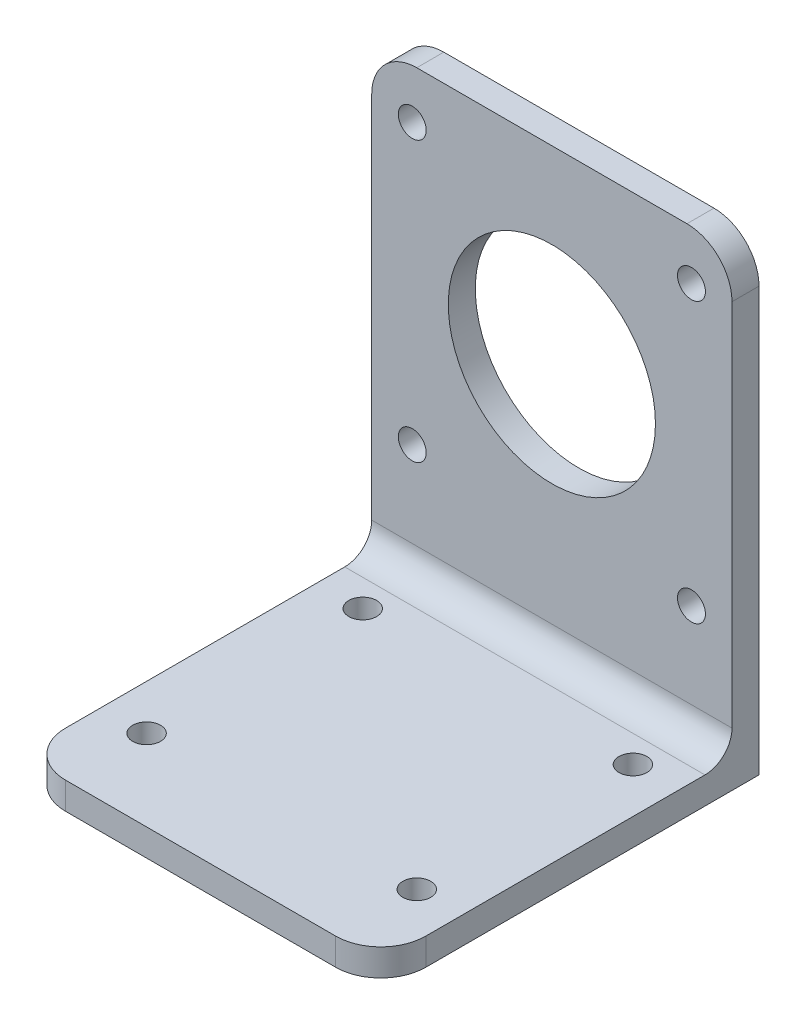
SolidWorks part; units mm, degrees
material "可锻铸铁"
ref_plane "前视基准面" through (0, 0, 0) normal (0, 0, 1) x (1, 0, 0)
ref_plane "上视基准面" through (0, 0, 0) normal (0, 1, 0) x (1, 0, 0)
ref_plane "右视基准面" through (0, 0, 0) normal (1, 0, 0) x (0, 0, -1)
sketch "草图1" plane through (0, 0, 0) normal (0, 1, 0) x (1, 0, 0)
  line L1 (-20, 21) -> (20, 21)
  line L2 (-20, 21) -> (-20, -21)
  line L3 (-20, -21) -> (20, -21)
  line L4 (20, 21) -> (20, -21)
  line L5 (-20, 21) -> (20, -21) construction
  line L6 (-20, -21) -> (20, 21) construction
  line L7 (-15, 12) -> (15, 12) construction
  line L8 (-15, 12) -> (-15, -12) construction
  line L9 (-15, -12) -> (15, -12) construction
  line L10 (15, 12) -> (15, -12) construction
  line L11 (-15, 12) -> (15, -12) construction
  line L12 (-15, -12) -> (15, 12) construction
  circle A0 centre (-15, -12) radius 1.55
  circle A1 centre (-15, 12) radius 1.55
  circle A2 centre (15, 12) radius 1.55
  circle A3 centre (15, -12) radius 1.55
  point P0 (0, 0)
  point P6 (0, 0)
  dimension "D5" = 3.1
  dimension "D6" = 3.1
  dimension "D7" = 3.1
  dimension "D8" = 3.1
  dimension "D1" = 40
  dimension "D2" = 42
  dimension "D3" = 30
  dimension "D4" = 24
extrude "凸台-拉伸1" add sketch "草图1" along normal blind 3
ref_plane "基准面1" through (0, 3, 0) normal (0, 1, 0) x (1, 0, 0)
sketch "草图2" plane through (0, 3, 0) normal (0, 1, 0) x (1, 0, 0)
  line L0 (20, -21) -> (20, 21) construction
  line L1 (-20, 21) -> (20, 21)
  line L2 (-20, 21) -> (-20, 18)
  line L3 (-20, 18) -> (20, 18)
  line L4 (20, 21) -> (20, 18)
  dimension "D1" = 3
extrude "凸台-拉伸2" add sketch "草图2" along normal blind 49
ref_plane "基准面2" through (0, 0, -18) normal (0, 0, 1) x (1, 0, 0)
sketch "草图3" plane through (0, 0, -18) normal (0, 0, 1) x (1, 0, 0)
  line L0 (-20, 0) -> (20, 0) construction
  line L2 (-15.5, 46.5) -> (15.5, 46.5) construction
  line L3 (-15.5, 46.5) -> (-15.5, 15.5) construction
  line L4 (-15.5, 15.5) -> (15.5, 15.5) construction
  line L5 (15.5, 46.5) -> (15.5, 15.5) construction
  line L6 (-15.5, 46.5) -> (15.5, 15.5) construction
  line L7 (-15.5, 15.5) -> (15.5, 46.5) construction
  circle A0 centre (0, 31) radius 11.5
  circle A1 centre (-15.5, 46.5) radius 1.55
  circle A2 centre (15.5, 46.5) radius 1.55
  circle A3 centre (15.5, 15.5) radius 1.55
  circle A4 centre (-15.5, 15.5) radius 1.55
  dimension "D2" = 23
  dimension "D5" = 3.1
  dimension "D6" = 3.1
  dimension "D7" = 3.1
  dimension "D8" = 3.1
  dimension "D1" = 31
  dimension "D3" = 31
  dimension "D4" = 31
extrude "切除-拉伸1" cut sketch "草图3" against normal blind 49
fillet "圆角1" radius 5 4 edges at (-20, 52, -19.5) (20, 52, -19.5) (20, 1.5, 21) (-20, 1.5, 21)
ref_plane "基准面3" through (-20, 0, 0) normal (-1, 0, 0) x (0, 0, 1)
fillet "圆角2" radius 3 1 edges at (0, 3, -18)
